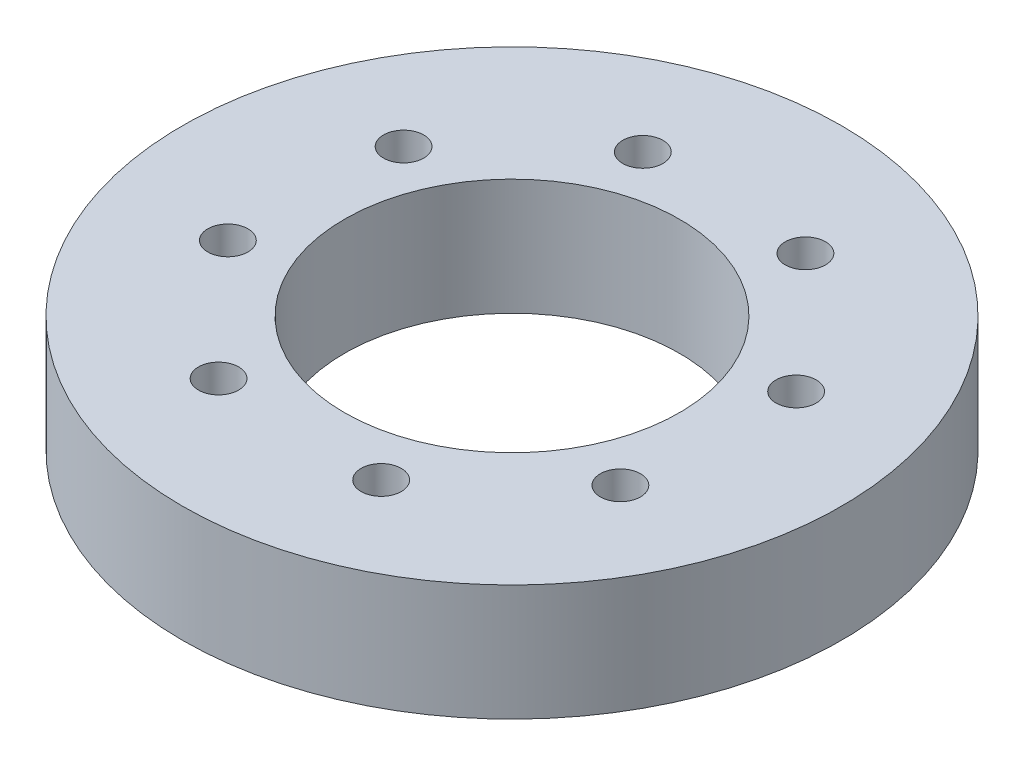
SolidWorks part; units mm, degrees
ref_plane "前视基准面" through (0, 0, 0) normal (0, 0, 1) x (1, 0, 0)
ref_plane "上视基准面" through (0, 0, 0) normal (0, 1, 0) x (1, 0, 0)
ref_plane "右视基准面" through (0, 0, 0) normal (1, 0, 0) x (0, 0, -1)
other "Configuration Table"
sketch "草图1" plane through (0, 0, 0) normal (0, 1, 0) x (1, 0, 0)
  circle A17 centre (0, 0) radius 14.75
  circle A18 centre (0, 0) radius 7.5
  dimension "D1" = 29.5
  dimension "D2" = 15
extrude "凸台-拉伸1" add sketch "草图1" along normal blind 5.2
sketch "草图2" plane through (0, -7.2, 0) normal (0, -1, 0) x (1, 0, 0)
  circle A1 centre (9.2861, -3.4305) radius 0.9
  point P2 (0, 0)
  dimension "D1" = 1.8
extrude "切除-拉伸1" cut sketch "草图2" against normal through all
pattern_circular "阵列(圆周)1" count 8 over 360 about axis through (0, 0, 0) along (0, 1, 0) of "切除-拉伸1"
